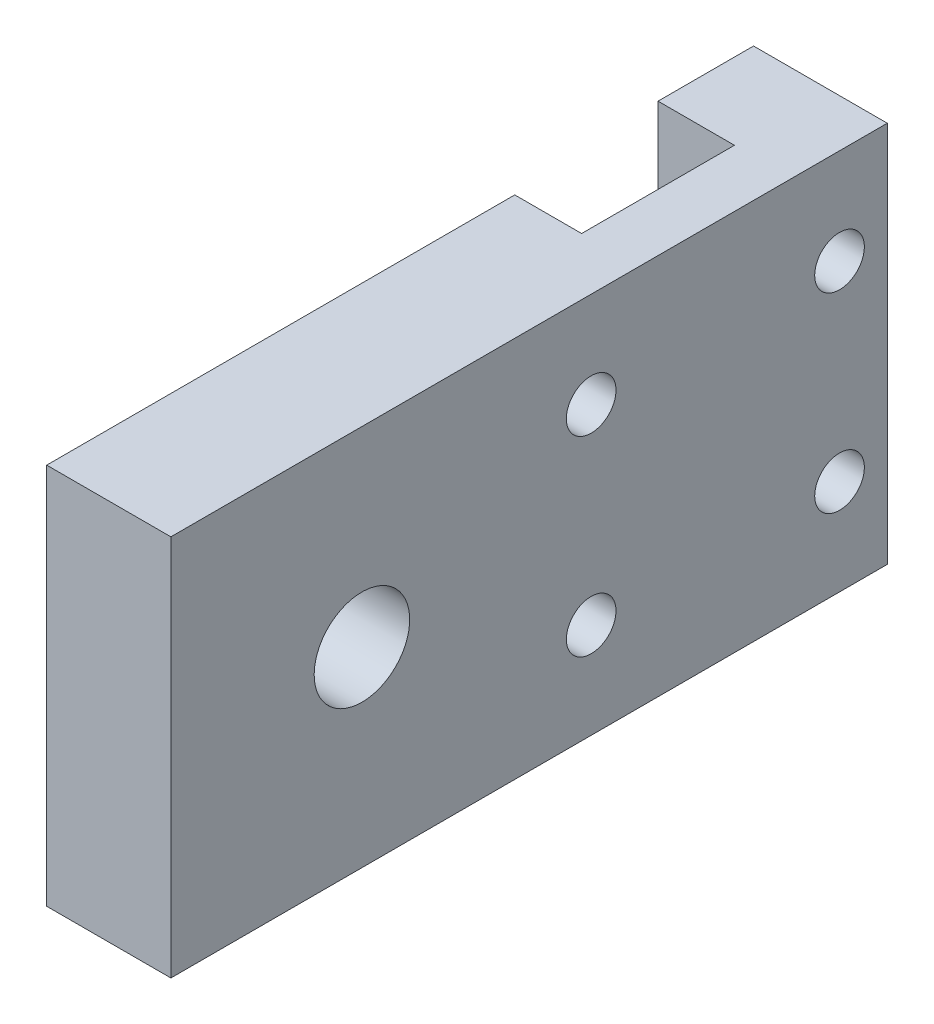
SolidWorks part; units mm, degrees
ref_plane "Front Plane" through (0, 0, 0) normal (1, 0, 0) x (0, 1, 0)
ref_plane "Top Plane" through (0, 0, 0) normal (0, 0, 1) x (0, 1, 0)
ref_plane "Right Plane" through (0, 0, 0) normal (0, 1, 0) x (-1, 0, 0)
sketch "Sketch1" plane through (0, 0, 0) normal (0, 1, 0) x (-1, 0, 0)
  line L0 (0, -5.0357) -> (0, -10.0357)
  line L1 (0, -10.0357) -> (-7, -10.0357)
  line L2 (-7, -10.0357) -> (-7, 5.9643)
  line L3 (-7, 5.9643) -> (-0.5, 5.9643)
  line L4 (-0.5, 5.9643) -> (-0.5, 2.9643)
  line L5 (-0.5, 2.9643) -> (-4, 2.9643)
  line L6 (-4, 2.9643) -> (-4, -5.0357)
  line L7 (-4, -5.0357) -> (0, -5.0357)
  dimension "D1" = 5
  dimension "D2" = 4
  dimension "D3" = 3
  dimension "D4" = 3
  dimension "D5" = 3.5
  dimension "D6" = 8
extrude "Boss-Extrude1" add sketch "Sketch1" along normal blind 20
sketch "Sketch2" plane through (0, 0, 0) normal (-1, 0, 0) x (0, -1, 0)
  line L0 (-20, -7.5357) -> (0, -7.5357) construction
  line L1 (-20, -10.0357) -> (-20, -5.0357) construction
  line L2 (0, -10.0357) -> (0, -5.0357) construction
  line L3 (-10, -5.0357) -> (-10, -10.0357) construction
  line L4 (-20, -5.0357) -> (0, -5.0357) construction
  line L5 (-20, -10.0357) -> (0, -10.0357) construction
  circle A0 centre (-15, -7.5357) radius 1.3
  circle A1 centre (-5, -7.5357) radius 1.3
  dimension "D2" = 2.6
  dimension "D1" = 5
extrude "Cut-Extrude1" cut sketch "Sketch2" against normal up to next
sketch "Sketch4" plane through (0, 20, 0) normal (0, 1, 0) x (-1, 0, 0)
  line L1 (-7, 5.9643) -> (-0.5, 5.9643)
  line L2 (-7, 5.9643) -> (-7, 27.4643)
  line L3 (-7, 27.4643) -> (-0.5, 27.4643)
  line L4 (-0.5, 5.9643) -> (-0.5, 27.4643)
  dimension "D1" = 6.5
  dimension "D2" = 21.5
extrude "Boss-Extrude2" add sketch "Sketch4" against normal blind 20
sketch "Sketch6" plane through (0.5, 0, 0) normal (-1, 0, 0) x (0, -1, 0)
  line L0 (-20, 5.4643) -> (0, 5.4643) construction
  line L3 (-20, 2.9643) -> (-20, 27.4643) construction
  line L4 (0, 2.9643) -> (0, 27.4643) construction
  line L5 (-20, 2.9643) -> (0, 2.9643) construction
  line L6 (-10, 27.4643) -> (-10, 2.9643) construction
  line L7 (0, 27.4643) -> (-20, 27.4643) construction
  line L8 (-20, 2.9643) -> (0, 2.9643) construction
  circle A0 centre (-15, 5.4643) radius 1.3
  circle A1 centre (-5, 5.4643) radius 1.3
  dimension "D2" = 2.6
  dimension "D1" = 2.5
  dimension "D3" = 5
extrude "Cut-Extrude2" cut sketch "Sketch6" against normal up to next
sketch "Sketch7" plane through (0.5, 0, 0) normal (-1, 0, 0) x (0, -1, 0)
  line L0 (-20, 17.4643) -> (0, 17.4643) construction
  circle A0 centre (-10, 17.4643) radius 2.5
  dimension "D1" = 5
  dimension "D2" = 14.5
extrude "Cut-Extrude3" cut sketch "Sketch7" against normal up to next
